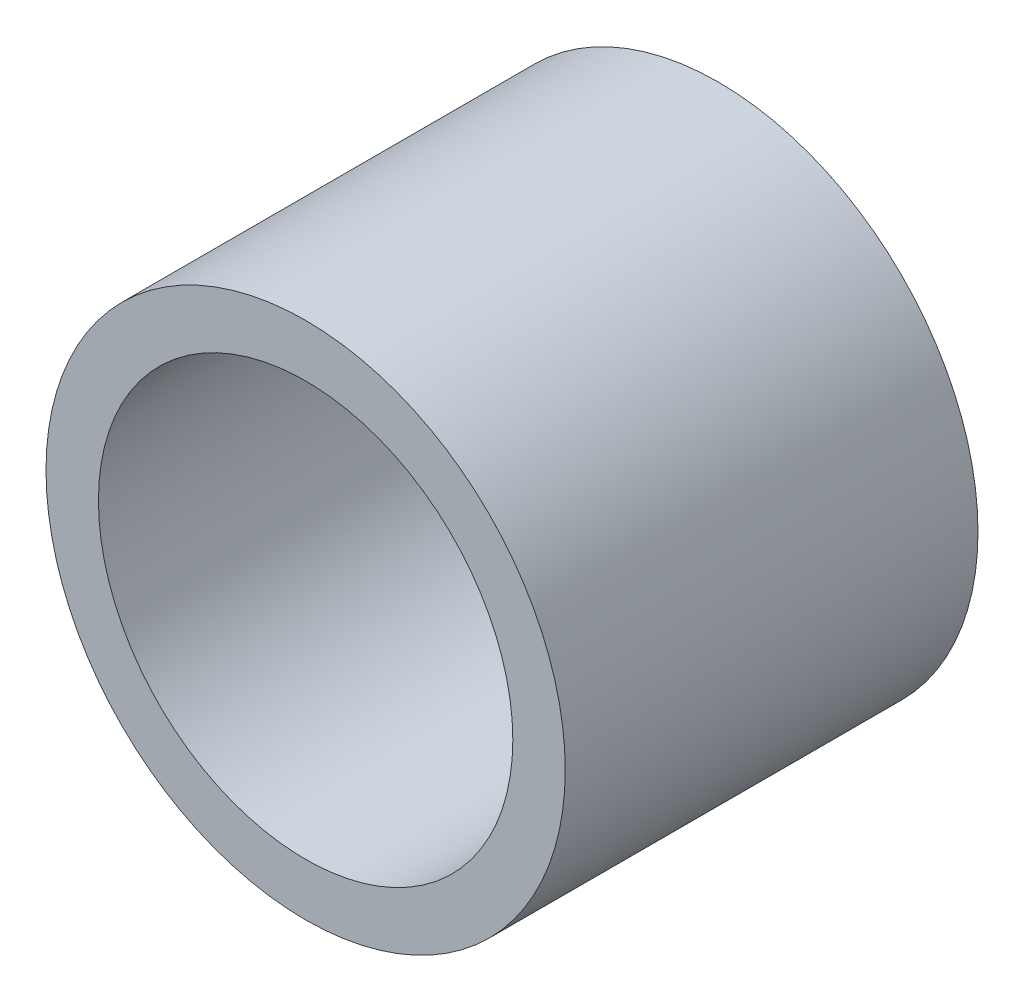
SolidWorks part; units mm, degrees
ref_plane "Front Plane" through (0, 0, 0) normal (0, 0, 1) x (1, 0, 0)
ref_plane "Top Plane" through (0, 0, 0) normal (0, 1, 0) x (1, 0, 0)
ref_plane "Right Plane" through (0, 0, 0) normal (1, 0, 0) x (0, 0, -1)
sketch "Sketch1" plane through (0, 0, 0) normal (0, 0, 1) x (1, 0, 0)
  circle A0 centre (0, 0) radius 3.9942
  circle A1 centre (0, 0) radius 3.1877
  dimension "OD" = 7.9883
  dimension "ID" = 6.3754
sketch "Sketch2" plane through (0, 0, 0) normal (1, 0, 0) x (0, 0, -1)
  line L2 (3.175, 0) -> (-3.175, 0) construction
  line L4 (-3.175, -3.9942) -> (-3.175, 3.9941) construction
  line L5 (-3.175, -3.1877) -> (3.175, -3.1877)
  line L6 (3.175, 3.1877) -> (-3.175, 3.1877)
  line L7 (3.175, -3.9942) -> (3.175, 3.9941) construction
  line L8 (-3.175, 3.9941) -> (3.175, 3.9941) construction
  line L9 (-3.175, -3.9942) -> (3.175, -3.9942) construction
  line L10 (0, 3.9942) -> (0, -3.9942) construction
  line L11 (0, 3.1877) -> (0, -3.1877) construction
  point P4 (0, -3.1877)
  point P7 (0, 3.1877)
  point P8 (0, 0)
  point P12 (-3.175, 0)
  point P15 (3.175, 0)
  point P16 (0, -3.9942)
  point P17 (0, 3.9942)
  dimension "Length" = 6.35
sketch "Sketch5" plane through (0, 0, 0) normal (0, 0, 1) x (1, 0, 0)
  circle A1 centre (0, 0) radius 3.1877
  circle A2 centre (0, 0) radius 3.1877
  circle A3 centre (0, 0) radius 3.9942
  circle A4 centre (0, 0) radius 3.9942
  dimension "D1" = 0
  dimension "D2" = 0
extrude "Boss-Extrude1" add sketch "Sketch5" along normal up to vertex (3.175 mm away) and the other way up to vertex (3.175 mm away) up to point (0, 0, 3.175) other way up to point (0, 0, -3.175)
sketch "Sketch4" plane through (0, 0, 3.175) normal (0, 0, 1) x (1, 0, 0)
  line L0 (0, 0) -> (-2.254, 2.254)
  line L2 (0, -3.9942) -> (0, 3.9941) construction
  circle A1 centre (0, 0) radius 3.1877 construction
  dimension "D1" = 45
equation "\"D1\"= \"Length@Sketch2\""
